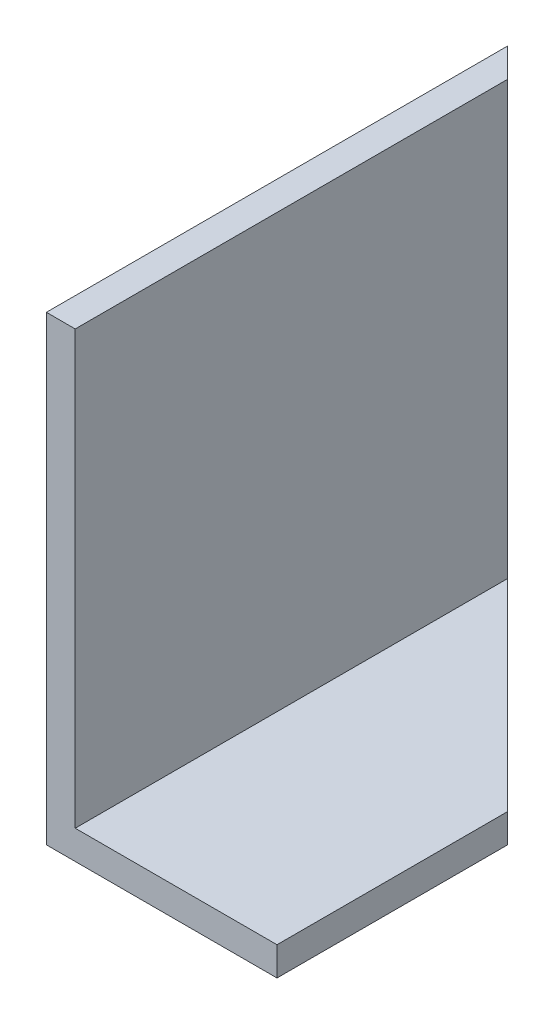
SolidWorks part; units mm, degrees
ref_plane "Front Plane" through (0, 0, 0) normal (0, 0, 1) x (1, 0, 0)
ref_plane "Top Plane" through (0, 0, 0) normal (0, 1, 0) x (1, 0, 0)
ref_plane "Right Plane" through (0, 0, 0) normal (1, 0, 0) x (0, 0, -1)
sketch "Sketch1" plane through (0, 0, 0) normal (0, 0, 1) x (1, 0, 0)
  line L0 (-9.525, -22.225) -> (12.7, -22.225)
  line L1 (-12.7, -25.4) -> (12.7, -25.4)
  line L2 (-12.7, -25.4) -> (-12.7, 25.4)
  line L3 (-9.525, -22.225) -> (-9.525, 25.4)
  line L4 (12.7, -25.4) -> (12.7, -22.225)
  line L5 (-12.7, 25.4) -> (-9.525, 25.4)
  dimension "D1" = 50.8
  dimension "D2" = 25.4
  dimension "D3" = 3.175
extrude "Boss-Extrude1" add sketch "Sketch1" along normal blind 50.8
sketch "Sketch6" plane through (0, -25.4, 0) normal (0, -1, 0) x (1, 0, 0)
  line L0 (-12.7, 0) -> (12.7, 25.4)
  line L1 (12.7, 50.8) -> (12.7, 0) construction
  line L2 (12.7, 25.4) -> (12.7, 0)
  line L3 (12.7, 0) -> (-12.7, 0)
  dimension "D1" = 45
extrude "Cut-Extrude4" cut sketch "Sketch6" against normal through all
